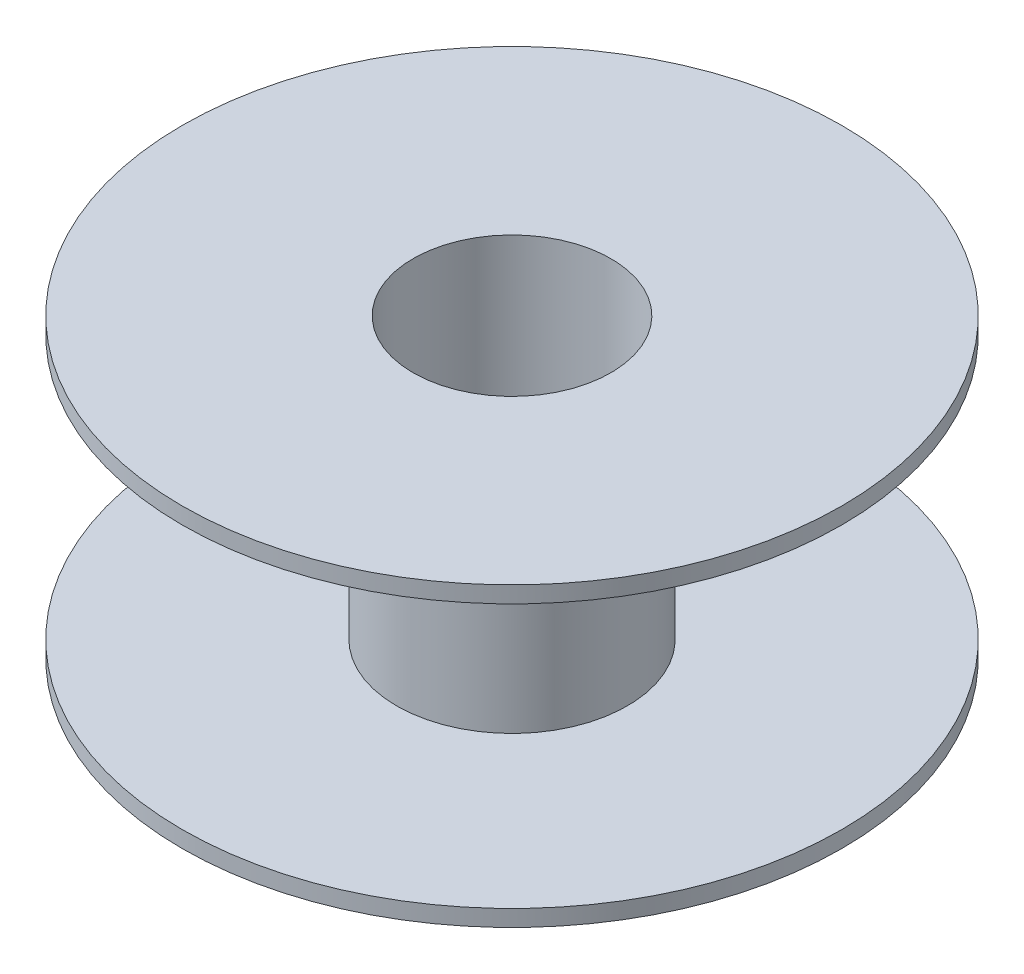
SolidWorks part; units mm, degrees
ref_plane "Front Plane" through (0, 0, 0) normal (0, 0, 1) x (1, 0, 0)
ref_plane "Top Plane" through (0, 0, 0) normal (0, 1, 0) x (1, 0, 0)
ref_plane "Right Plane" through (0, 0, 0) normal (1, 0, 0) x (0, 0, -1)
sketch "Sketch1" plane through (0, 0, 0) normal (0, 1, 0) x (1, 0, 0)
  circle A0 centre (0, 0) radius 100
  circle A1 centre (0, 0) radius 30
  dimension "D1" = 200
  dimension "D2" = 60
extrude "Boss-Extrude1" add sketch "Sketch1" along normal blind 5
sketch "Sketch2" plane through (0, 5, 0) normal (0, 1, 0) x (1, 0, 0)
  circle A0 centre (0, 0) radius 30
  circle A1 centre (0, 0) radius 35
  circle A2 centre (0, 0) radius 30 construction
  dimension "D1" = 5
  dimension "D2" = 0
extrude "Boss-Extrude2" add sketch "Sketch2" along normal blind 40
mirror "Mirror1" about plane through (0, 45, 0) normal (0, 1, 0) of "Boss-Extrude2", "Boss-Extrude1"
